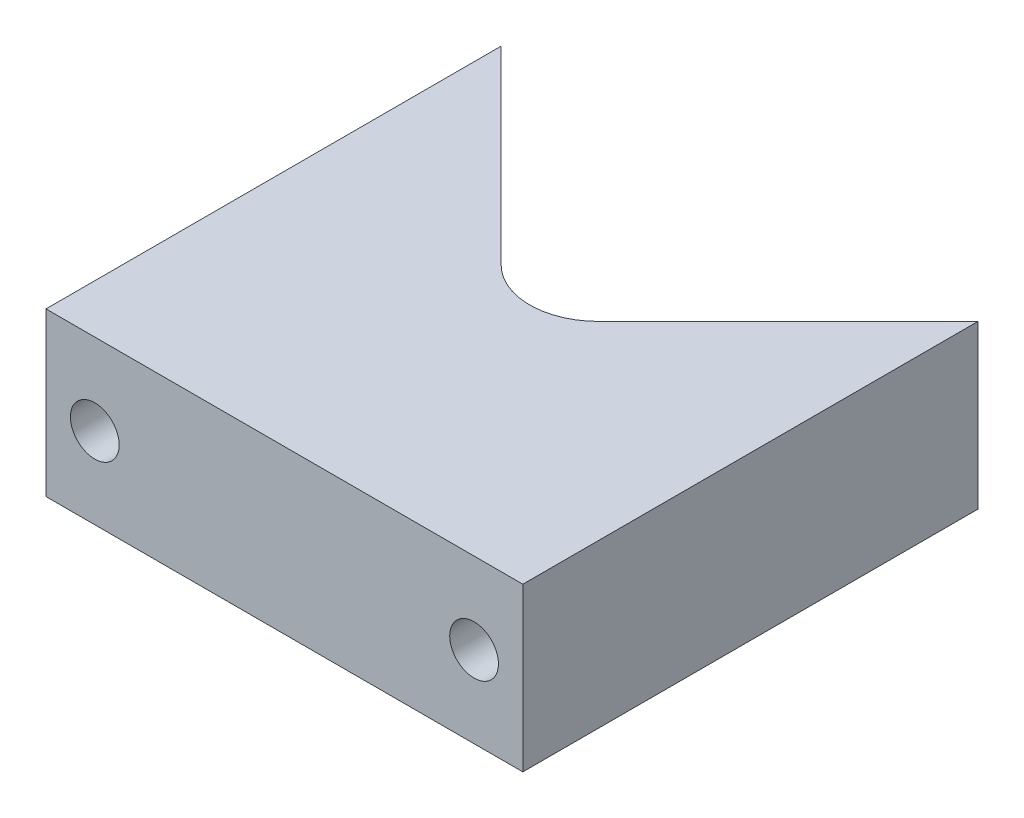
SolidWorks part; units mm, degrees
material "6061 Alloy"
ref_plane "Front" through (0, 0, 0) normal (0, 0, 1) x (1, 0, 0)
ref_plane "Top" through (0, 0, 0) normal (0, 1, 0) x (1, 0, 0)
ref_plane "Right" through (0, 0, 0) normal (1, 0, 0) x (0, 0, -1)
sketch "Sketch1" plane through (0, 0, 0) normal (0, 1, 0) x (1, 0, 0)
  line L0 (0, 0) -> (0, 42)
  line L1 (0, -50) -> (0, 50) construction
  line L2 (0, 42) -> (22, 20)
  line L3 (22, 20) -> (44, 42)
  line L4 (44, 42) -> (44, 0)
  line L5 (44, 0) -> (0, 0)
  dimension "D1" = 44
  dimension "D2" = 42
  dimension "D3" = 90
extrude "Boss-Extrude1" add sketch "Sketch1" along normal blind 15
ref_plane "Plane1" through (0, 0, -12.7) normal (0, 0, -1) x (-1, 0, 0)
hole_wizard "M4 Clearance Hole5" positions "Sketch10" profile "Sketch11" hole size "M4" standard "ANSI Metric"
sketch "Sketch10" plane through (0, 0, -12.7) normal (0, 0, -1) x (-1, 0, 0)
  line L0 (-4.5, 15) -> (-4.5, 0) construction
  line L1 (-22, 15) -> (0, 15) construction
  line L2 (50, 0) -> (-50, 0) construction
  line L5 (-39.5, 15) -> (-39.5, 0) construction
  line L6 (-44, 15) -> (-22, 15) construction
  line L8 (-39.5, 7.5) -> (-44, 7.5) construction
  line L9 (-44, 15) -> (-44, 0) construction
  line L11 (-4.5, 7.5) -> (0, 7.5) construction
  line L12 (0, 50) -> (0, -50) construction
  point P0 (-39.5, 7.5)
  point P2 (-4.5, 7.5)
  dimension "D1" = 35
sketch "Sketch11" plane through (39.5, 7.5, -12.7) normal (1, 0, 0) x (0, 1, 0)
  line L0 (0, 0) -> (0, 12.7)
  line L1 (0, 12.7) -> (2.25, 12.7)
  line L2 (2.25, 12.7) -> (2.25, 0)
  line L5 (2.25, 0) -> (0, 0)
  line L11 (0, -6.35) -> (0, 107.95) construction
  dimension "Thru Hole Dia." = 4.5
  dimension "Thru Hole Depth" = 12.7
hole_wizard "Ø6.0mm Dowel Hole1" positions "Sketch12" profile "Sketch13" hole size "Ø6.0" standard "ANSI Metric"
sketch "Sketch12" plane through (0, 0, -12.7) normal (0, 0, -1) x (-1, 0, 0)
  line L0 (-44, 7.5) -> (-39.5, 7.5) construction
  line L1 (-44, 15) -> (-44, 0) construction
  line L3 (0, 7.5) -> (-4.5, 7.5) construction
  line L4 (0, 50) -> (0, -50) construction
  point P0 (-39.5, 7.5)
  point P2 (-4.5, 7.5)
  dimension "D1" = 35
sketch "Sketch13" plane through (39.5, 7.5, -12.7) normal (1, 0, 0) x (0, -1, 0)
  line L0 (0, 0) -> (0, 29.3)
  line L1 (0, 29.3) -> (3.75, 29.3)
  line L2 (3.75, 29.3) -> (3.75, 0)
  line L5 (3.75, 0) -> (0, 0)
  line L11 (0, -6.35) -> (0, 107.95) construction
  dimension "Thru Hole Dia." = 7.5
  dimension "Thru Hole Depth" = 29.3
fillet "Fillet1" radius 6.35 1 edges at (22, 7.5, -20)
